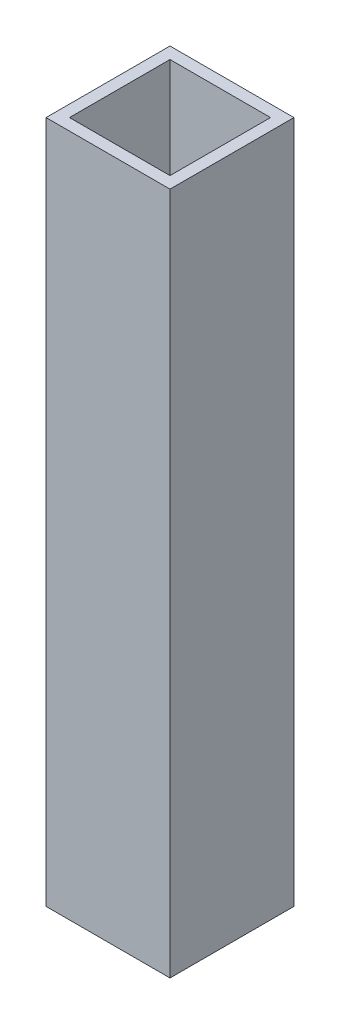
SolidWorks part; units mm, degrees
ref_plane "Alzado" through (0, 0, 0) normal (0, 0, 1) x (1, 0, 0)
ref_plane "Planta" through (0, 0, 0) normal (0, 1, 0) x (1, 0, 0)
ref_plane "Vista lateral" through (0, 0, 0) normal (1, 0, 0) x (0, 0, -1)
sketch "Croquis1" plane through (0, 0, 0) normal (0, 1, 0) x (1, 0, 0)
  line L1 (-6.35, 6.35) -> (6.35, 6.35)
  line L2 (-6.35, 6.35) -> (-6.35, -6.35)
  line L3 (-6.35, -6.35) -> (6.35, -6.35)
  line L4 (6.35, 6.35) -> (6.35, -6.35)
  line L5 (-6.35, 6.35) -> (6.35, -6.35) construction
  line L6 (-6.35, -6.35) -> (6.35, 6.35) construction
  point P0 (0, 0)
  dimension "D1" = 12.7
extrude "Extruir-Lámina1" add sketch "Croquis1" along normal blind 70 thin
equation "\"tibia\"= 70"
